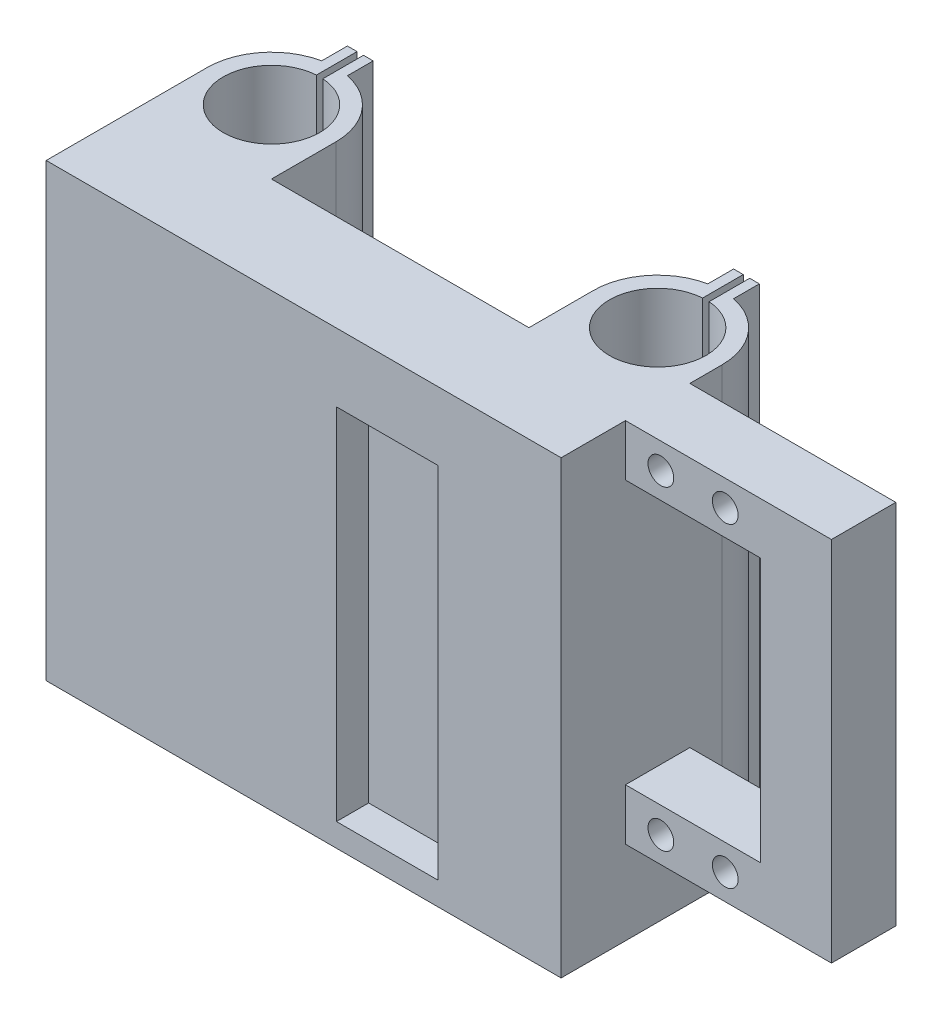
SolidWorks part; units mm, degrees
ref_plane "Alzado" through (0, 0, 0) normal (0, 0, 1) x (1, 0, 0)
ref_plane "Planta" through (0, 0, 0) normal (0, 1, 0) x (1, 0, 0)
ref_plane "Vista lateral" through (0, 0, 0) normal (1, 0, 0) x (0, 0, -1)
sketch "Croquis1" plane through (0, 0, 0) normal (0, 1, 0) x (1, 0, 0)
  line L0 (-58.0166, 0) -> (58.0166, 0) construction
  line L5 (40, -25) -> (40, 0)
  line L6 (11.3137, 4) -> (20.8348, 4)
  line L7 (0, 33.1459) -> (0, -45.5761) construction
  line L8 (-40, -25) -> (-40, 0)
  line L9 (-11.3137, 4) -> (-20.8348, 4)
  line L10 (-40, -25) -> (40, -25)
  arc A1 (11.3137, 4) -> (-11.3137, 4) centre (0, 0) ccw
  arc A2 (40, 0) -> (20.8348, 4) centre (30, 0) ccw
  arc A3 (-40, 0) -> (-20.8348, 4) centre (-30, 0) cw
  point P3 (0, 0)
  dimension "D1" = 20
  dimension "D2" = 24
  dimension "D3" = 30
  dimension "D4" = 4
  dimension "D5" = 25
extrude "Saliente-Extruir1" add sketch "Croquis1" along normal blind 70
sketch "Croquis3" plane through (0, 70, 0) normal (0, 1, 0) x (1, 0, 0)
  line L0 (-30, 0) -> (-30, 16.5211) construction
  line L1 (-32, 9.798) -> (-32, 13.798)
  line L2 (-32, 13.798) -> (-28, 13.798)
  line L3 (-28, 9.798) -> (-28, 13.798)
  line L4 (0, -55) -> (0, 55) construction
  line L5 (28, 9.798) -> (28, 13.798)
  line L6 (32, 13.798) -> (28, 13.798)
  line L7 (32, 9.798) -> (32, 13.798)
  arc A0 (-20.8348, 4) -> (-40, 0) centre (-30, 0) ccw construction
  arc A1 (-28, 9.798) -> (-32, 9.798) centre (-30, 0) ccw
  arc A2 (28, 9.798) -> (32, 9.798) centre (30, 0) cw
  point P10 (-30, 13.798)
  dimension "D1" = 4
  dimension "D2" = 4
extrude "Saliente-Extruir2" add sketch "Croquis3" against normal up to surface (70 mm away) up to face at (0, 0, 1.3027)
sketch "Croquis4" plane through (0, 70, 0) normal (0, 1, 0) x (1, 0, 0)
  line L0 (-30.5, 7.4833) -> (-30.5, 14.6548)
  line L1 (-30, 0) -> (-30, 16.6168) construction
  line L2 (-30.5, 14.6548) -> (-29.5, 14.6548)
  line L3 (-29.5, 7.4833) -> (-29.5, 14.6548)
  line L4 (0, -55) -> (0, 55) construction
  line L5 (29.5, 7.4833) -> (29.5, 14.6548)
  line L6 (30.5, 14.6548) -> (29.5, 14.6548)
  line L7 (30.5, 7.4833) -> (30.5, 14.6548)
  arc A1 (-30.5, 7.4833) -> (-29.5, 7.4833) centre (-30, 0) ccw
  arc A2 (30.5, 7.4833) -> (29.5, 7.4833) centre (30, 0) cw
  point P8 (-30, 14.6548)
  point P16 (30, 14.6548)
  dimension "D1" = 15
  dimension "D2" = 1
extrude "Cortar-Extruir2" cut sketch "Croquis4" against normal through all both and the other way through all
sketch "Croquis5" plane through (0, 70, 0) normal (0, 1, 0) x (1, 0, 0)
  line L0 (-20, 0) -> (-20, -10)
  line L1 (-20, -10) -> (20, -10)
  line L2 (0, 31.6012) -> (0, -31.6012) construction
  line L3 (-20, -10) -> (-30, -10) construction
  line L7 (20, 0) -> (20, -10)
  line L8 (-20.8348, 4) -> (-20.8348, 13.996)
  line L9 (-20.8348, 13.996) -> (20.8348, 13.996)
  line L10 (20.8348, 13.996) -> (20.8348, 4)
  arc A0 (11.3137, 4) -> (-11.3137, 4) centre (0, 0) ccw construction
  arc A3 (-32, 9.798) -> (-40, 0) centre (-30, 0) ccw construction
  arc A4 (-32, 9.798) -> (-40, 0) centre (-30, 0) ccw construction
  arc A5 (-20, 0) -> (-20.8348, 4) centre (-30, 0) ccw
  arc A6 (-32, 9.798) -> (-40, 0) centre (-30, 0) ccw construction
  arc A7 (20, 0) -> (20.8348, 4) centre (30, 0) cw
  point P9 (0, 0)
  point P16 (0, -10)
extrude "Cortar-Extruir3" cut sketch "Croquis5" against normal blind 30
sketch "Croquis9" plane through (0, 0, 0) normal (0, 1, 0) x (1, 0, 0)
  line L0 (-20, 0) -> (-20, -10)
  line L1 (-20, -10) -> (20, -10)
  line L2 (0, 31.6012) -> (0, -31.6012) construction
  line L3 (-20, -10) -> (-30, -10) construction
  line L7 (20, 0) -> (20, -10)
  line L8 (-20.8348, 4) -> (-20.8348, 13.996)
  line L9 (-20.8348, 13.996) -> (20.8348, 13.996)
  line L10 (20.8348, 13.996) -> (20.8348, 4)
  arc A4 (-32, 9.798) -> (-40, 0) centre (-30, 0) ccw construction
  arc A5 (-20, 0) -> (-20.8348, 4) centre (-30, 0) ccw
  arc A6 (-32, 9.798) -> (-40, 0) centre (-30, 0) ccw construction
  arc A7 (20, 0) -> (20.8348, 4) centre (30, 0) cw
  point P16 (0, -10)
extrude "Cortar-Extruir6" cut sketch "Croquis9" along normal blind 30 contours L9 L10 A7 L7 L1 L0 A5 L8
sketch "Croquis6" plane through (0, 70, 0) normal (0, 1, 0) x (1, 0, 0)
  line L0 (0, 0) -> (-12.9386, 12.9386) construction
  line L1 (0, 0) -> (0, 16.0434) construction
  circle A0 centre (0, 0) radius 5
  circle A1 centre (-6.0104, 6.0104) radius 1.6
  circle A2 centre (6.0104, 6.0104) radius 1.6
  circle A3 centre (6.0104, -6.0104) radius 1.6
  circle A4 centre (-6.0104, -6.0104) radius 1.6
  point P16 (0, 0)
  dimension "D1" = 10
  dimension "D3" = 3.2
  dimension "D4" = 8.5
  dimension "D2" = 45
  dimension "D5" = 4
extrude "Cortar-Extruir4" cut sketch "Croquis6" against normal through all both and the other way through all
sketch "Croquis7" plane through (40, 0, 0) normal (1, 0, 0) x (0, 0, -1)
  line L0 (-15, 70) -> (-15, 62)
  line L1 (-25, 70) -> (0, 70) construction
  line L2 (-15, 62) -> (-5, 62)
  line L3 (-35.4515, 41.5) -> (26.4894, 41.5) construction
  line L4 (-5, 62) -> (-5, 70)
  line L5 (-5, 70) -> (-15, 70)
  line L6 (-25, 70) -> (-25, 0) construction
  line L7 (-5, 13) -> (-15, 13)
  line L8 (-5, 21) -> (-5, 13)
  line L9 (-15, 21) -> (-5, 21)
  line L10 (-15, 13) -> (-15, 21)
  dimension "D1" = 8
  dimension "D2" = 20.5
  dimension "D3" = 10
  dimension "D4" = 10
extrude "Saliente-Extruir3" add sketch "Croquis7" along normal blind 32
sketch "Croquis8" plane through (0, 0, 15) normal (0, 0, 1) x (1, 0, 0)
  line L0 (50.5, 62) -> (50.5, 21) construction
  line L1 (72, 62) -> (40, 62) construction
  line L2 (49.485, 41.5) -> (51.515, 41.5) construction
  line L3 (72, 21) -> (40, 21) construction
  line L7 (40, 70) -> (40, 0) construction
  circle A0 centre (45.5, 66) radius 2
  circle A1 centre (55.5, 66) radius 2
  circle A2 centre (45.5, 17) radius 2
  circle A3 centre (55.5, 17) radius 2
  point P9 (50.5, 41.5)
  dimension "D1" = 10
  dimension "D2" = 4
  dimension "D3" = 5.5
  dimension "D4" = 49
extrude "Cortar-Extruir5" cut sketch "Croquis8" against normal through all both and the other way through all
sketch "Croquis10" plane through (0, 62, 0) normal (0, -1, 0) x (1, 0, 0)
  line L0 (61, 5) -> (61, 15)
  line L1 (72, 5) -> (40, 5) construction
  line L2 (72, 15) -> (40, 15) construction
  line L3 (61, 15) -> (72, 15)
  line L4 (72, 15) -> (72, 5) construction
  line L5 (72, 15) -> (72, 5)
  line L6 (72, 5) -> (61, 5)
  dimension "D1" = 11
extrude "Saliente-Extruir4" add sketch "Croquis10" along normal up to next
sketch "Croquis12" plane through (0, 0, 25) normal (0, 0, 1) x (1, 0, 0)
  line L0 (5.5, 59) -> (5.5, 4) construction
  line L1 (20.5, 59) -> (5.5, 59) construction
  line L2 (20.5, 59) -> (20.5, 4) construction
  line L3 (20.5, 4) -> (5.5, 4) construction
  line L4 (5.5, 59) -> (5.5, 4) construction
  line L5 (20.5, 59) -> (5.5, 59) construction
  line L6 (20.5, 59) -> (20.5, 4) construction
  line L7 (20.5, 4) -> (5.5, 4) construction
  line L8 (5.1, 59.4) -> (5.1, 3.6)
  line L9 (20.9, 3.6) -> (5.1, 3.6)
  line L10 (20.9, 59.4) -> (20.9, 3.6)
  line L11 (20.9, 59.4) -> (5.1, 59.4)
  dimension "D1" = 0.4
extrude "Cortar-Extruir7" cut sketch "Croquis12" against normal blind 5
